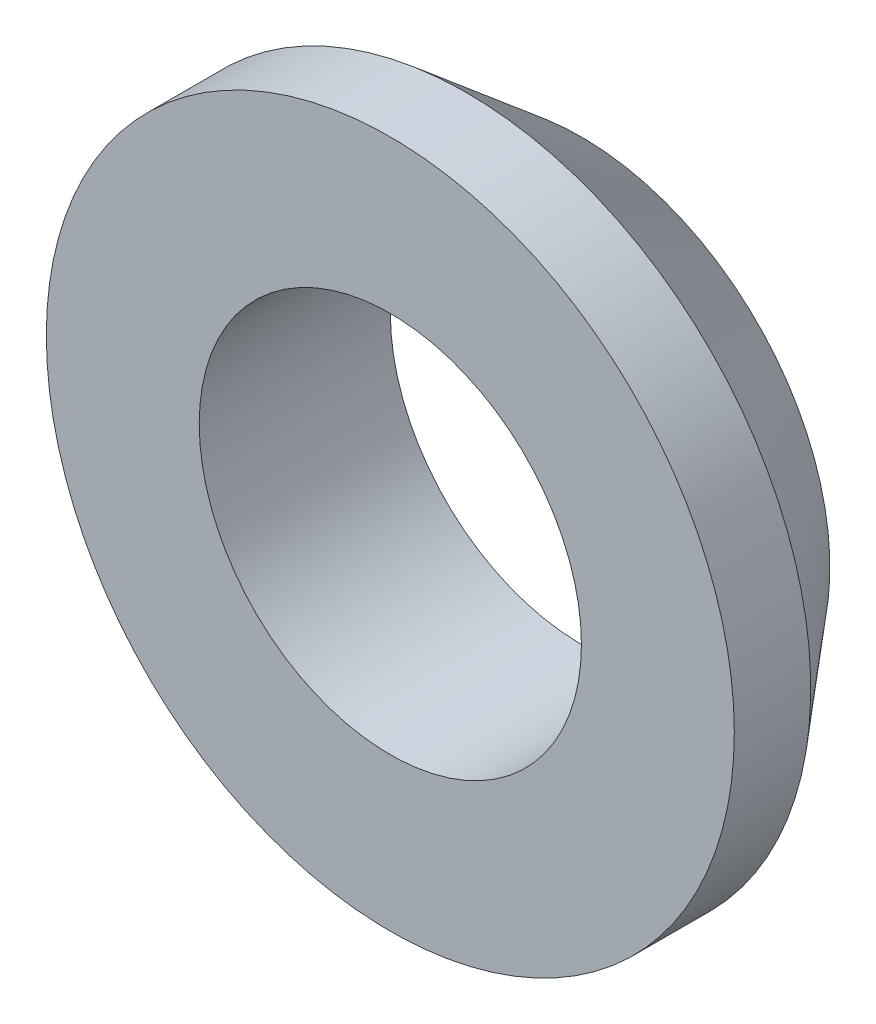
SolidWorks part; units mm, degrees
ref_plane "Płaszczyzna przednia" through (0, 0, 0) normal (0, 0, 1) x (1, 0, 0)
ref_plane "Płaszczyzna górna" through (0, 0, 0) normal (0, 1, 0) x (1, 0, 0)
ref_plane "Płaszczyzna prawa" through (0, 0, 0) normal (1, 0, 0) x (0, 0, -1)
sketch "Sketch1" plane through (0, 0, 0) normal (0, 0, 1) x (1, 0, 0)
  circle A0 centre (0, 0) radius 5
  circle A1 centre (0, 0) radius 9
  dimension "D1" = 10
  dimension "D2" = 18
extrude "Boss-Extrude1" add sketch "Sketch1" along normal blind 2
ref_plane "Plane1" through (0, 0, -3) normal (0, 0, -1) x (-1, 0, 0)
sketch "Sketch2" plane through (0, 0, -3) normal (0, 0, -1) x (-1, 0, 0)
  circle A0 centre (0, 0) radius 5
  circle A1 centre (0, 0) radius 6.5
  dimension "D1" = 10
  dimension "D2" = 1.5
sketch "Sketch3" plane through (0, 0, 0) normal (0, 0, -1) x (-1, 0, 0)
  circle A0 centre (0, 0) radius 5 construction
  circle A1 centre (0, 0) radius 9
  circle A2 centre (0, 0) radius 9
  circle A3 centre (0, 0) radius 5
  dimension "D1" = 0
loft "Loft1" add section "Sketch3" section "Sketch2"
sketch "Sketch4" plane through (0, 0, -3) normal (0, 0, -1) x (-1, 0, 0)
  circle A0 centre (0, 0) radius 5
  dimension "D1" = 10
extrude "Cut-Extrude1" cut sketch "Sketch4" against normal up to surface (5 mm away) up to face at (9, 0, 2)
